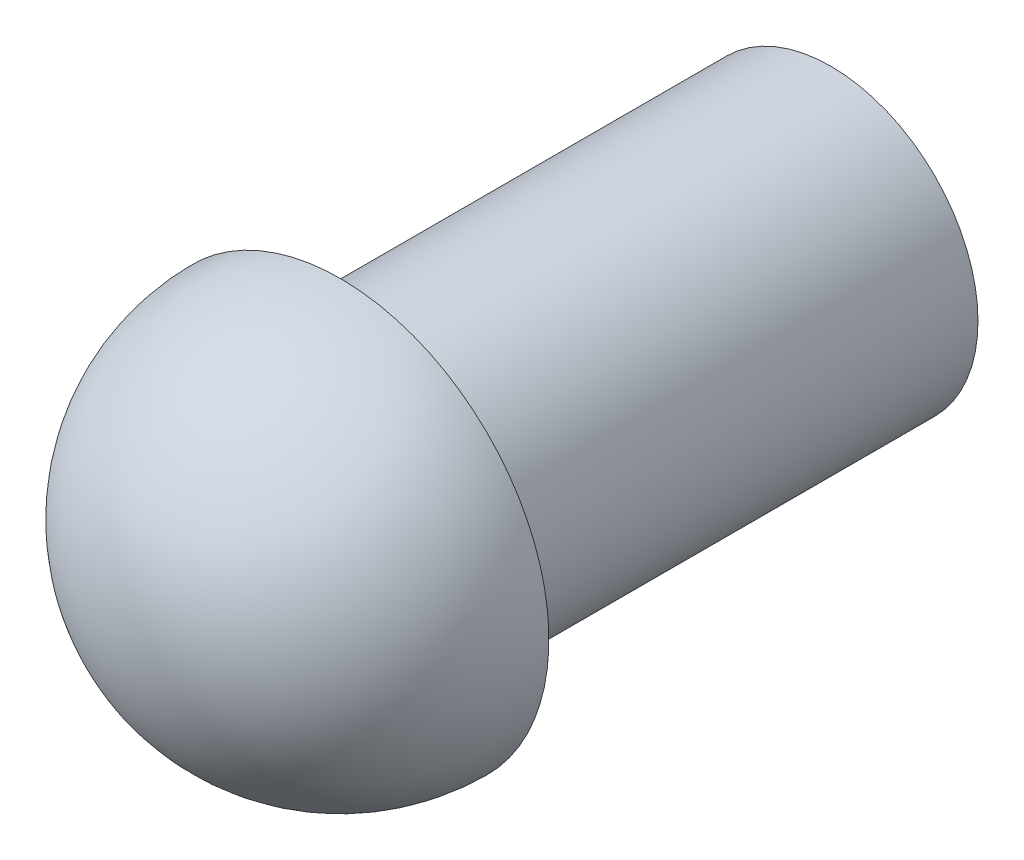
SolidWorks part; units mm, degrees
ref_plane "Plan de face" through (0, 0, 0) normal (0, 0, 1) x (1, 0, 0)
ref_plane "Plan de dessus" through (0, 0, 0) normal (0, 1, 0) x (1, 0, 0)
ref_plane "Plan de droite" through (0, 0, 0) normal (1, 0, 0) x (0, 0, -1)
sketch "Esquisse1" plane through (0, 0, 0) normal (0, 0, 1) x (1, 0, 0)
  circle A0 centre (0, 0) radius 3
  dimension "D1" = 6
extrude "Boss.-Extru.1" add sketch "Esquisse1" along normal blind 10
sketch "Esquisse3" plane through (0, 0, 10) normal (0, 0, 1) x (1, 0, 0)
  line L0 (0, -4.25) -> (0, 4.25)
  arc A0 (0, 4.25) -> (0, -4.25) centre (0, 0) ccw
  dimension "D1" = 8.5
revolve "Révolution1" add sketch "Esquisse3" angle 180 about L0
